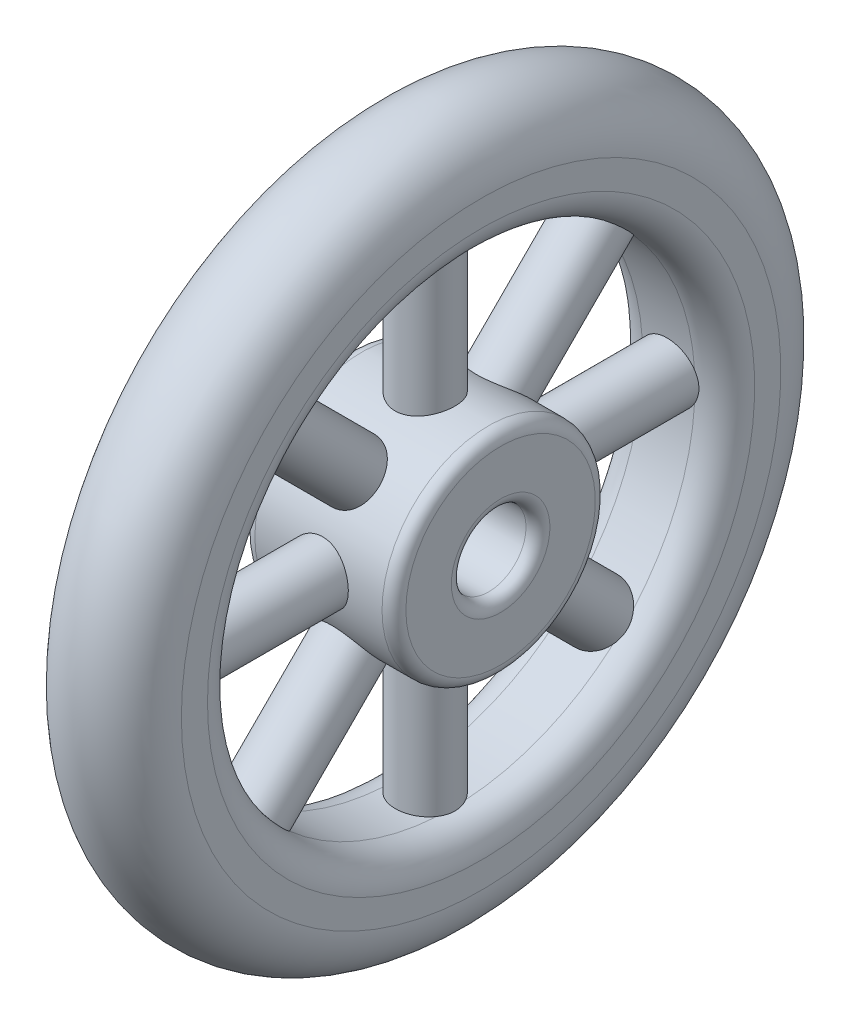
SolidWorks part; units mm, degrees
material "ABS"
ref_plane "Front Plane" through (0, 0, 0) normal (0, 0, 1) x (1, 0, 0)
ref_plane "Top Plane" through (0, 0, 0) normal (0, 1, 0) x (1, 0, 0)
ref_plane "Right Plane" through (0, 0, 0) normal (1, 0, 0) x (0, 0, -1)
sketch "Sketch3" plane through (0, 0, 0) normal (0, 0, 1) x (1, 0, 0)
  line L2 (13.3734, 0) -> (-13.3734, 0) construction
  line L4 (0, 1.5875) -> (0, 15.1331) construction
  line L5 (-2.7042, 1.5875) -> (2.7042, 1.5875)
  line L6 (2.7042, 4.5382) -> (-2.7042, 4.5382)
  line L7 (0, -8.3232) -> (0, 8.3232) construction
  line L8 (-11.9772, 0) -> (12.3381, 0) construction
  line L11 (3.2122, 2.0955) -> (3.2122, 4.0302)
  line L13 (-3.2122, 2.0955) -> (-3.2122, 4.0302)
  line L14 (-2.3813, 12.7518) -> (-2.3813, 11.6406)
  line L15 (-1.1112, 10.3706) -> (1.1112, 10.3706)
  line L16 (2.3812, 11.6406) -> (2.3812, 12.7518)
  arc A0 (2.3812, 12.7518) -> (-2.3813, 12.7518) centre (0, 12.7518) ccw
  arc A1 (1.1112, 10.3706) -> (2.3812, 11.6406) centre (1.1112, 11.6406) ccw
  arc A2 (-1.1112, 10.3706) -> (-2.3813, 11.6406) centre (-1.1113, 11.6406) cw
  arc A3 (-3.2122, 2.0955) -> (-2.7042, 1.5875) centre (-2.7042, 2.0955) ccw
  arc A4 (-3.2122, 4.0302) -> (-2.7042, 4.5382) centre (-2.7042, 4.0302) cw
  arc A5 (3.2122, 2.0955) -> (2.7042, 1.5875) centre (2.7042, 2.0955) cw
  arc A6 (3.2122, 4.0302) -> (2.7042, 4.5382) centre (2.7042, 4.0302) ccw
  dimension "D1" = 4.7625
  dimension "D2" = 1.27
  dimension "D3" = 0.508
  dimension "D4" = 3.2122
  dimension "D5" = 1.5875
  dimension "D6" = 4.5382
  dimension "D7" = 10.3706
revolve "Revolve1" add sketch "Sketch3" angle 360 about L8
sketch "Sketch5" plane through (0, 0, 0) normal (1, 0, 0) x (0, 0, -1)
  line L0 (0, 3.0628) -> (0, 12.7518)
  line L1 (0, 2.0955) -> (0, 4.0302) construction
  point P4 (0, 0)
  point P5 (0, 3.4951)
sweep "Sweep1" add path "Sketch5" circular profile diameter 2.54 parameters "D3"=2.54
pattern_circular "CirPattern1" count 8 over 360 about axis through (-11.9772, 0, 0) along (1, 0, 0) of "Sweep1"
